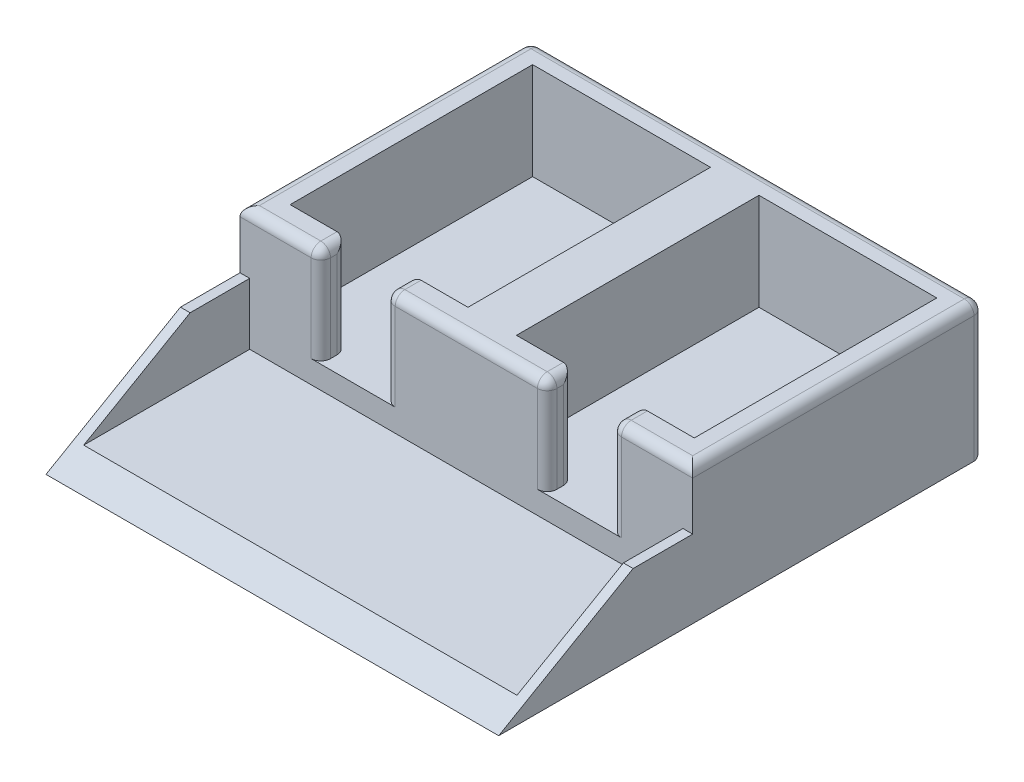
SolidWorks part; units mm, degrees
ref_plane "Front Plane" through (0, 0, 0) normal (0, 0, 1) x (1, 0, 0)
ref_plane "Top Plane" through (0, 0, 0) normal (0, 1, 0) x (1, 0, 0)
ref_plane "Right Plane" through (0, 0, 0) normal (1, 0, 0) x (0, 0, -1)
sketch "Sketch1" plane through (0, 0, 0) normal (0, 1, 0) x (1, 0, 0)
  line L0 (0, 0) -> (140, 0)
  line L1 (-55, 0) -> (55, 0) construction
  line L2 (140, 0) -> (140, 90)
  line L3 (140, 90) -> (0, 90)
  line L4 (0, -55) -> (0, 55) construction
  line L5 (0, 90) -> (0, 0)
  line L6 (70, 90) -> (70, 0) construction
  dimension "D1" = 140
  dimension "D2" = 90
extrude "Boss-Extrude1" add sketch "Sketch1" along normal blind 42
ref_plane "Plane1" through (0, 42, 0) normal (0, 1, 0) x (1, 0, 0)
sketch "Sketch2" plane through (0, 42, 0) normal (0, 1, 0) x (1, 0, 0)
  line L0 (7.5, 8) -> (7.5, 83)
  line L1 (0, 0) -> (140, 0) construction
  line L2 (7.5, 83) -> (62.5, 83)
  line L3 (62.5, 83) -> (62.5, 8)
  line L5 (70, 90) -> (70, 0) construction
  line L6 (140, 90) -> (0, 90) construction
  line L7 (77.5, 8) -> (77.5, 83)
  line L8 (77.5, 83) -> (132.5, 83)
  line L9 (132.5, 83) -> (132.5, 8)
  line L11 (25, 8) -> (25, 0)
  line L12 (7.5, 8) -> (25, 8)
  line L13 (0, 90) -> (0, 0) construction
  line L14 (25, 0) -> (45, 0)
  line L15 (45, 0) -> (45, 8)
  line L17 (95, 8) -> (95, 0)
  line L18 (95, 0) -> (115, 0)
  line L19 (115, 0) -> (115, 8)
  line L21 (45, 8) -> (62.5, 8)
  line L22 (77.5, 8) -> (95, 8)
  line L23 (115, 8) -> (132.5, 8)
  dimension "D1" = 55
  dimension "D2" = 55
  dimension "D3" = 15
  dimension "D4" = 7.5
  dimension "D5" = 75
  dimension "D6" = 75
  dimension "D7" = 20
  dimension "D8" = 17.5
  dimension "D9" = 20
  dimension "D10" = 17.5
extrude "Cut-Extrude1" cut sketch "Sketch2" against normal blind 30
fillet "Fillet2" radius 3 21 edges at (12.5, 42, 0) (0, 42, -45) (140, 21, -90) (140, 42, -45) (127.5, 42, 0) (115, 27, 0) (115, 27, -8) (115, 42, -4) (95, 42, -4) (95, 27, -8) (25, 27, -8) (45, 27, -8) (45, 42, -4) (25, 42, -4) (45, 27, 0) (25, 27, 0) (95, 27, 0) (70, 42, 0) (70, 42, -90) (0, 21, -90) (70, 0, -90)
sketch "Sketch3" plane through (0, 0, 0) normal (0, 1, 0) x (1, 0, 0)
  line L1 (0, 0) -> (140, 0)
  line L2 (0, 0) -> (0, -60)
  line L3 (0, -60) -> (140, -60)
  line L4 (140, 0) -> (140, -60)
  line L5 (140, 0) -> (140, 87) construction
  point P5 (0, 0)
  dimension "D1" = 60
extrude "Boss-Extrude2" add sketch "Sketch3" along normal blind 5
sketch "Sketch4" plane through (0, 5, 0) normal (0, 1, 0) x (1, 0, 0)
  line L0 (0, -60) -> (140, -60) construction
  line L1 (0, 0) -> (3, 0)
  line L2 (0, 0) -> (0, -60)
  line L3 (0, -60) -> (3, -60)
  line L4 (3, 0) -> (3, -60)
  line L6 (140, 0) -> (137, 0)
  line L7 (140, 0) -> (140, -60)
  line L8 (140, -60) -> (137, -60)
  line L9 (137, 0) -> (137, -60)
  dimension "D1" = 3
  dimension "D2" = 3
extrude "Boss-Extrude3" add sketch "Sketch4" along normal blind 19
sketch "Sketch5" plane through (0, 0, 0) normal (-1, 0, 0) x (0, 0, 1)
  line L0 (60, 0) -> (8.0385, 30)
  line L1 (-87, 0) -> (60, 0) construction
  line L2 (8.0385, 30) -> (60, 30)
  line L3 (60, 30) -> (60, 0)
  dimension "D1" = 60
  dimension "D2" = 30
extrude "Cut-Extrude2" cut sketch "Sketch5" against normal through all both and the other way through all
